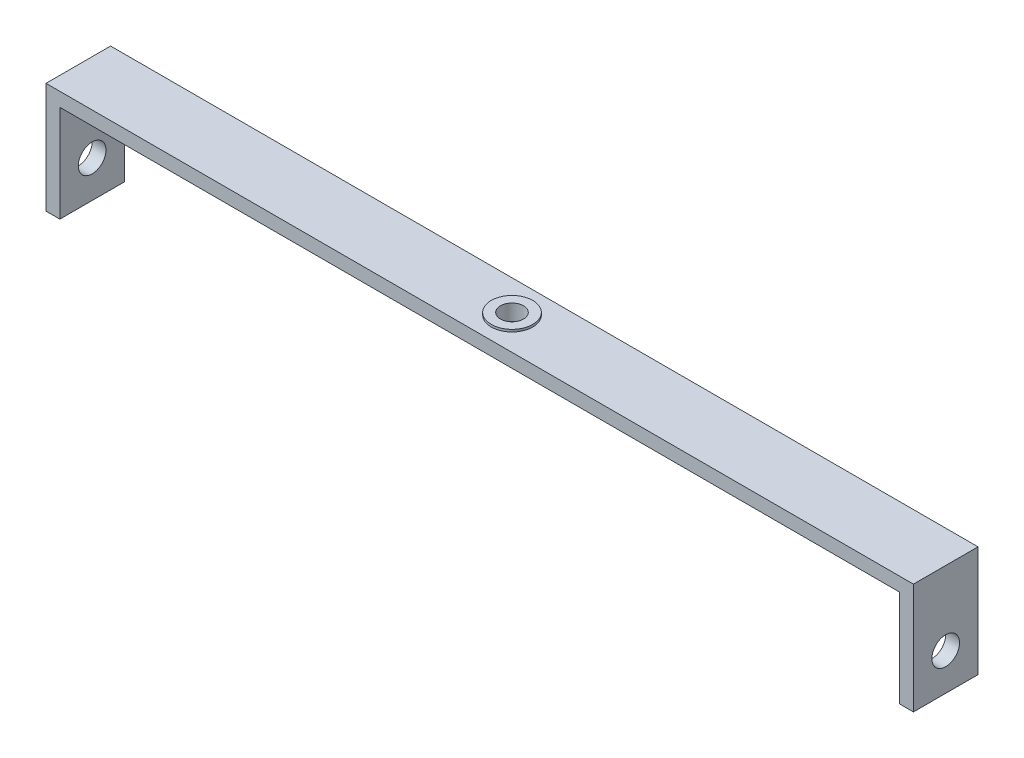
SolidWorks part; units mm, degrees
ref_plane "Front Plane" through (0, 0, 0) normal (0, 0, 1) x (1, 0, 0)
ref_plane "Top Plane" through (0, 0, 0) normal (0, 1, 0) x (1, 0, 0)
ref_plane "Right Plane" through (0, 0, 0) normal (1, 0, 0) x (0, 0, -1)
sketch "Sketch1" plane through (0, 0, 0) normal (0, 0, 1) x (1, 0, 0)
  line L0 (-47, -12) -> (-47, 0)
  line L1 (-47, 0) -> (47, 0)
  line L2 (47, 0) -> (47, -12)
  line L3 (-45.5, -12) -> (-45.5, -1.5)
  line L4 (-45.5, -1.5) -> (45.5, -1.5)
  line L5 (45.5, -1.5) -> (45.5, -12)
  line L6 (-47, -12) -> (-45.5, -12)
  line L7 (45.5, -12) -> (47, -12)
  point P2 (0, 0)
  dimension "D1" = 94
  dimension "D2" = 12
  dimension "D3" = 1.5
extrude "Boss-Extrude1" add sketch "Sketch1" along normal mid plane 7
sketch "Sketch2" plane through (0, 0, 0) normal (0, 1, 0) x (1, 0, 0)
  circle A0 centre (0, 0) radius 1.25
  dimension "D1" = 2.5
extrude "Cut-Extrude1" cut sketch "Sketch2" against normal up to surface (1.5 mm away) and the other way through all up to face at (0, -1.5, 0)
sketch "Sketch3" plane through (0, 0, 0) normal (0, 1, 0) x (1, 0, 0)
  circle A0 centre (0, 0) radius 1.25 construction
  circle A1 centre (0, 0) radius 1.25
  circle A2 centre (0, 0) radius 2.25
  dimension "D1" = 1
extrude "Boss-Extrude2" add sketch "Sketch3" along normal mid plane 0.5
sketch "Sketch4" plane through (0, 0, 0) normal (1, 0, 0) x (0, 0, -1)
  line L0 (0, 0) -> (0, -8) construction
  circle A0 centre (0, -8) radius 1.5
  dimension "D1" = 3
  dimension "D2" = 8
extrude "Cut-Extrude2" cut sketch "Sketch4" against normal through all both and the other way through all
scale "Scale1" scale about centroid uniform scaling yes scale factor 18
